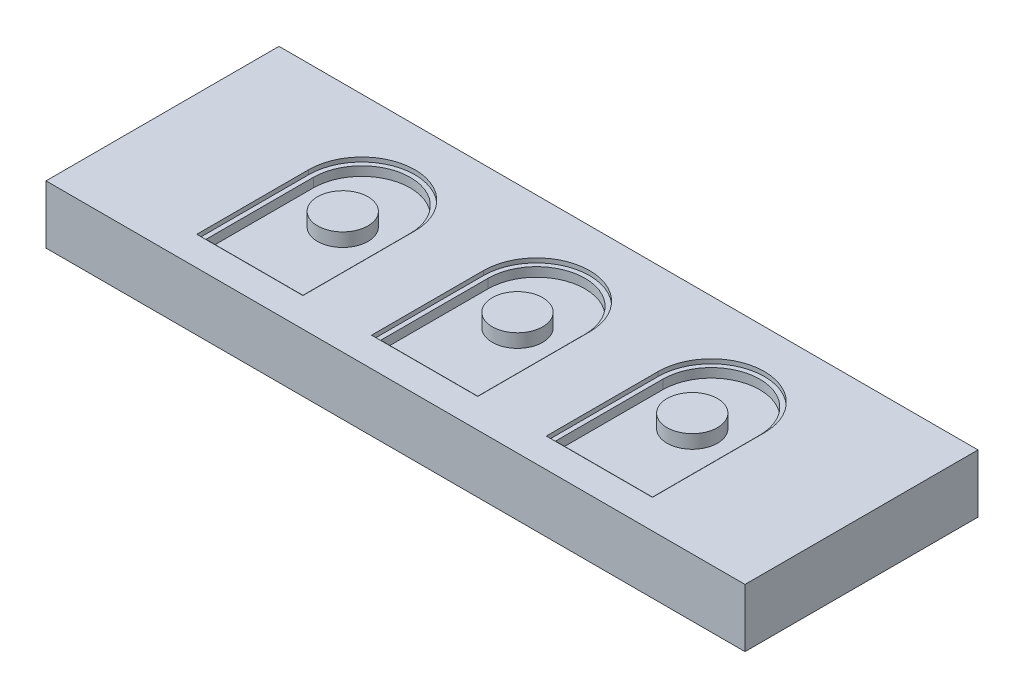
SolidWorks part; units mm, degrees
ref_plane "Front Plane" through (0, 0, 0) normal (0, 0, 1) x (1, 0, 0)
ref_plane "Top Plane" through (0, 0, 0) normal (0, 1, 0) x (1, 0, 0)
ref_plane "Right Plane" through (0, 0, 0) normal (1, 0, 0) x (0, 0, -1)
sketch "Sketch1" plane through (0, 0, 0) normal (0, 1, 0) x (1, 0, 0)
  line L1 (0, 0) -> (152.4, 0)
  line L2 (0, 0) -> (0, 50.8)
  line L3 (0, 50.8) -> (152.4, 50.8)
  line L4 (152.4, 0) -> (152.4, 50.8)
extrude "Boss-Extrude1" add sketch "Sketch1" along normal blind 12.7
sketch "Sketch2" plane through (0, 12.7, 0) normal (0, 1, 0) x (1, 0, 0)
  line L0 (64.627, 30.75) -> (64.627, 6.35)
  line L1 (64.627, 6.35) -> (87.773, 6.35)
  line L2 (87.773, 6.35) -> (87.773, 30.75)
  line L3 (0, 0) -> (152.4, 0) construction
  arc A0 (87.773, 30.75) -> (64.627, 30.75) centre (76.2, 30.75) ccw
  point P5 (76.2, 6.35)
  point P8 (76.2, 0)
  dimension "D1" = 23.146
  dimension "D2" = 24.4
  dimension "D3" = 6.35
extrude "Cut-Extrude1" cut sketch "Sketch2" against normal blind 0.95
sketch "Sketch3" plane through (0, 11.75, 0) normal (0, 1, 0) x (1, 0, 0)
  line L9 (65.627, 30.75) -> (65.627, 7.35)
  line L10 (65.627, 7.35) -> (86.773, 7.35)
  line L11 (86.773, 7.35) -> (86.773, 30.75)
  line L12 (65.627, 30.75) -> (65.627, 7.35)
  line L13 (65.627, 7.35) -> (86.773, 7.35)
  line L14 (86.773, 7.35) -> (86.773, 30.75)
  arc A3 (86.773, 30.75) -> (65.627, 30.75) centre (76.2, 30.75) ccw
  arc A4 (86.773, 30.75) -> (65.627, 30.75) centre (76.2, 30.75) ccw
  dimension "D1" = 1
extrude "Cut-Extrude2" cut sketch "Sketch3" against normal blind 2
sketch "Sketch4" plane through (0, 9.75, 0) normal (0, 1, 0) x (1, 0, 0)
  line L0 (65.627, 7.35) -> (86.773, 7.35) construction
  line L2 (64.627, 6.35) -> (87.773, 6.35) construction
  circle A0 centre (76.2, 26.6) radius 5.5
  point P4 (0, 0)
  point P9 (76.2, 6.35)
  dimension "D1" = 19.25
  dimension "D2" = 11
extrude "Boss-Extrude2" add sketch "Sketch4" along normal up to surface (2.95 mm away) up to face at (76.2, 12.7, -21.4433)
pattern_linear "LPattern1" count 2 spacing 38.1 along (1, 0, 0) count 2 spacing 38.1 along (-1, 0, 0) of "Cut-Extrude2", "Cut-Extrude1", "Boss-Extrude2"
